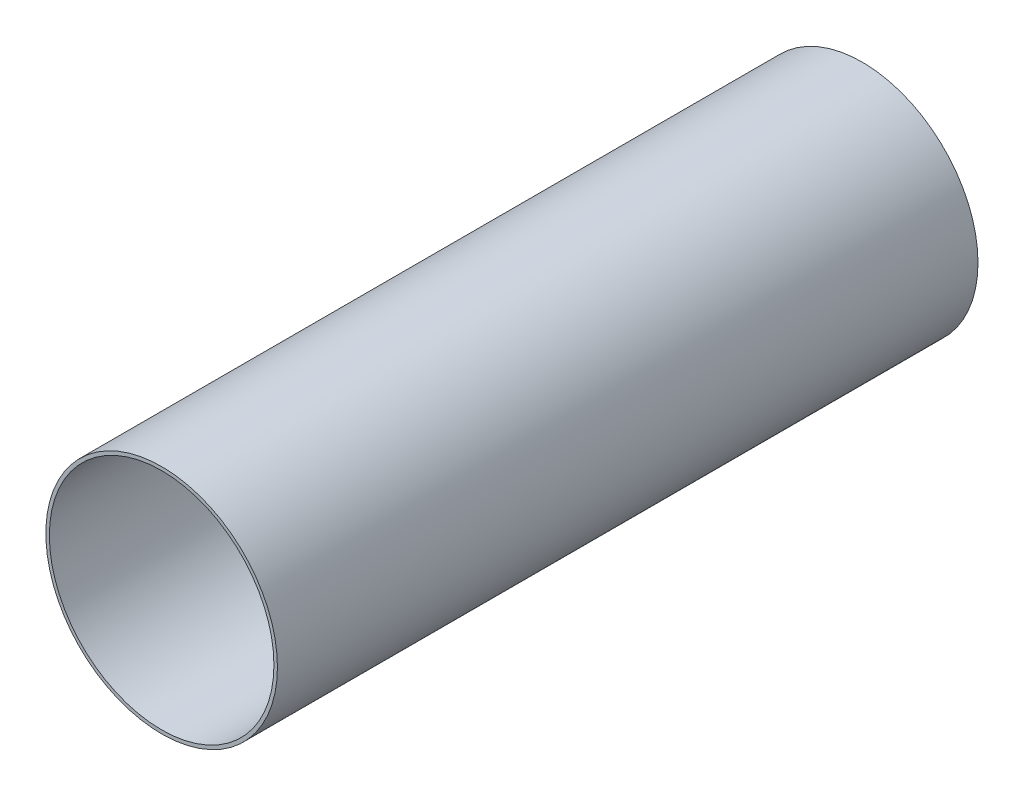
SolidWorks part; units mm, degrees
material "Corrugated Paper"
ref_plane "Front Plane" through (0, 0, 0) normal (0, 0, 1) x (1, 0, 0)
ref_plane "Top Plane" through (0, 0, 0) normal (0, 1, 0) x (1, 0, 0)
ref_plane "Right Plane" through (0, 0, 0) normal (1, 0, 0) x (0, 0, -1)
sketch "Sketch1" plane through (0, 0, 0) normal (0, 0, 1) x (1, 0, 0)
  circle A0 centre (0, 0) radius 32.5374
  circle A1 centre (0, 0) radius 31.5531
  dimension "D1" = 65.0748
  dimension "D2" = 0.9842
extrude "Boss-Extrude1" add sketch "Sketch1" along normal up to surface (196.85 mm away)
